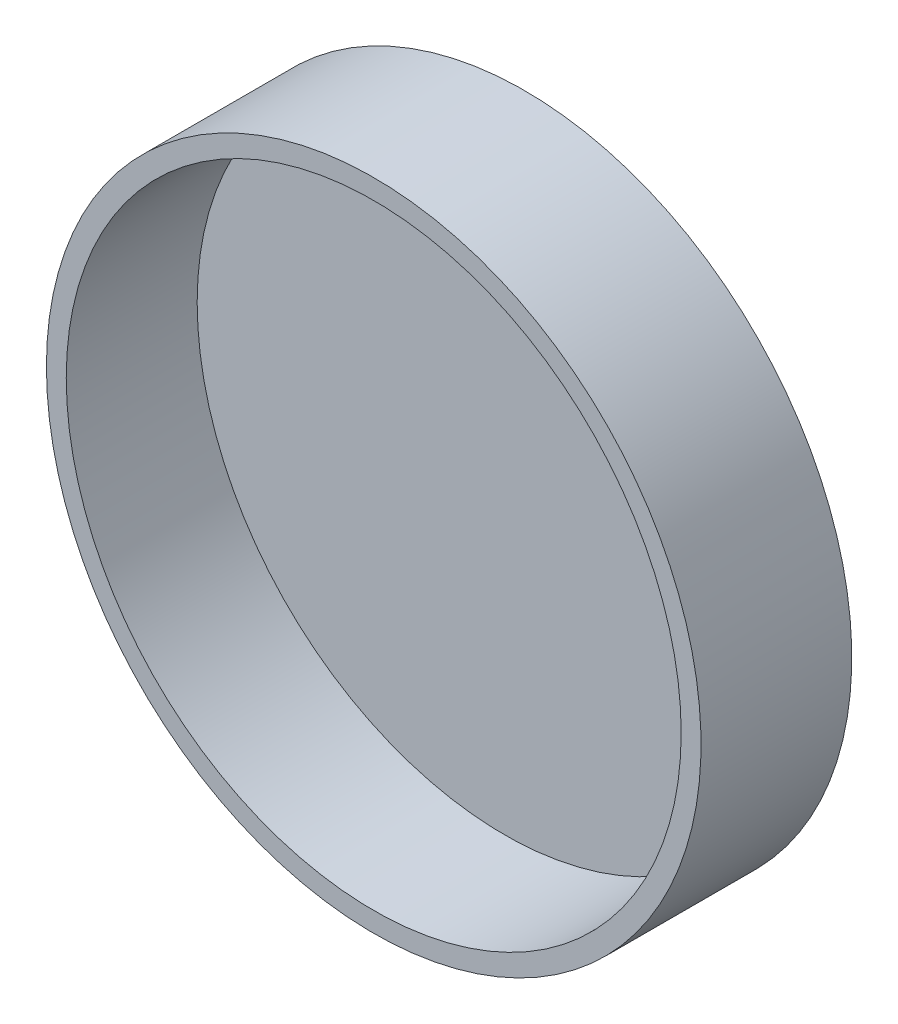
SolidWorks part; units mm, degrees
material "PA Type 6"
ref_plane "Front Plane" through (0, 0, 0) normal (0, 0, 1) x (1, 0, 0)
ref_plane "Top Plane" through (0, 0, 0) normal (0, 1, 0) x (1, 0, 0)
ref_plane "Right Plane" through (0, 0, 0) normal (1, 0, 0) x (0, 0, -1)
sketch "Sketch1" plane through (0, 0, 0) normal (0, 0, 1) x (1, 0, 0)
  circle A0 centre (0, 0) radius 16.5
  dimension "D1" = 33
extrude "Boss-Extrude1" add sketch "Sketch1" along normal blind 7.6
shell "Shell1" thickness 1
